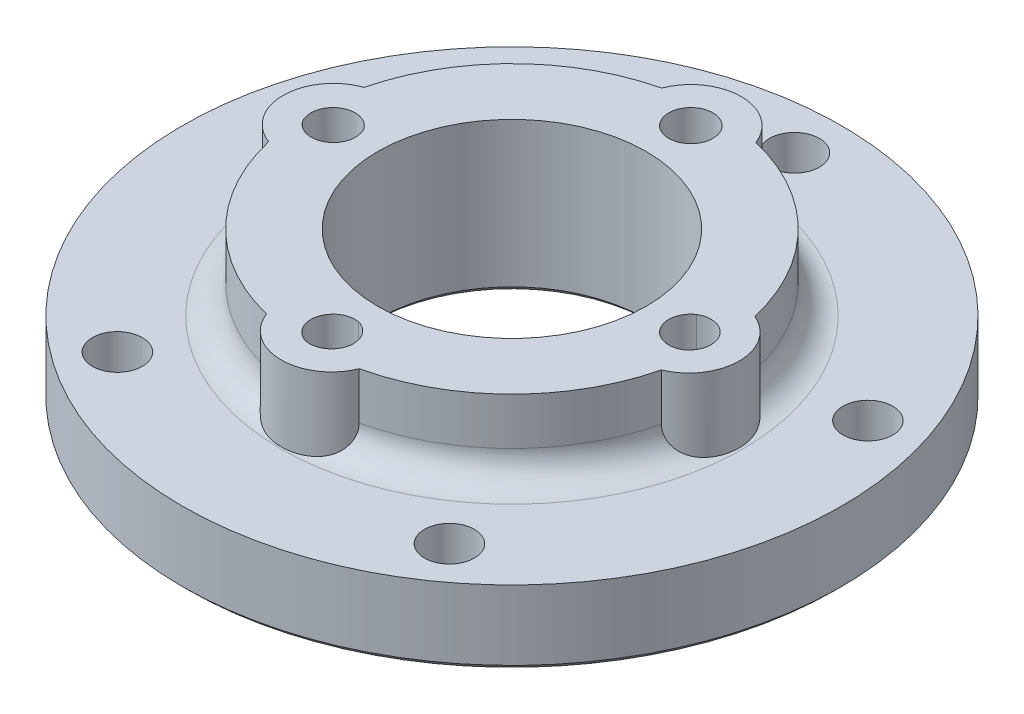
SolidWorks part; units mm, degrees
material "PETG"
ref_plane "Front Plane" through (0, 0, 0) normal (0, 0, 1) x (1, 0, 0)
ref_plane "Top Plane" through (0, 0, 0) normal (0, 1, 0) x (1, 0, 0)
ref_plane "Right Plane" through (0, 0, 0) normal (1, 0, 0) x (0, 0, -1)
sketch "Sketch2" plane through (0, 0, 0) normal (0, 1, 0) x (1, 0, 0)
  circle A0 centre (0, 0) radius 35
  circle A1 centre (0, 0) radius 30 construction
  circle A2 centre (0, 0) radius 21
  circle A3 centre (0, 30) radius 2.65
  circle A4 centre (28.5317, 9.2705) radius 2.65
  circle A5 centre (17.6336, -24.2705) radius 2.65
  circle A6 centre (-17.6336, -24.2705) radius 2.65
  circle A7 centre (-28.5317, 9.2705) radius 2.65
  point P22 (0, 0)
  dimension "D1" = 70
  dimension "D2" = 60
  dimension "D3" = 42
  dimension "D4" = 5.3
  dimension "D5" = 5
extrude "Boss-Extrude6" add sketch "Sketch2" along normal blind 8 separate body
sketch "Sketch3" plane through (0, 0, 0) normal (0, 1, 0) x (1, 0, 0)
  circle A0 centre (0, 0) radius 21 construction
  circle A1 centre (0, 0) radius 21 construction
  circle A2 centre (0, 0) radius 21.5
  circle A5 centre (0, 0) radius 14.25
  dimension "D1" = 28.5
  dimension "D2" = 0.5
extrude "Boss-Extrude7" add sketch "Sketch3" along normal blind 16
fillet "Fillet1" radius 3 1 edges at (0, 8, 21.5)
sketch "Sketch4" plane through (0, 16, 0) normal (0, 1, 0) x (1, 0, 0)
  circle A2 centre (0, 19) radius 2.35
  circle A5 centre (19, 0) radius 2.35
  circle A6 centre (0, -19) radius 2.35
  circle A7 centre (-19, 0) radius 2.35
  circle A8 centre (0, 0) radius 19 construction
  point P14 (0, 0)
  dimension "D1" = 38
  dimension "D2" = 4.7
  dimension "D3" = 4
extrude "Cut-Extrude1" cut sketch "Sketch4" against normal blind 15
sketch "Sketch7" plane through (0, 16, 0) normal (0, 1, 0) x (1, 0, 0)
  line L0 (-4.4779, 16.0723) -> (4.398, 15.9537)
  line L1 (15.9468, 4.3958) -> (15.8282, -4.4801)
  line L2 (4.2702, -16.0289) -> (-4.6057, -15.9103)
  line L3 (-16.1544, -4.3523) -> (-16.0358, 4.5236)
  circle A0 centre (18.8745, -0.0821) radius 2.35
  arc A1 (15.8282, -4.4801) -> (15.9468, 4.3958) centre (18.8745, -0.0821) ccw
  circle A2 centre (0, 19) radius 2.35 construction
  circle A3 centre (0, 19) radius 5.35
  arc A4 (4.398, 15.9537) -> (-4.4779, 16.0723) centre (0, 19) ccw
  circle A5 centre (0, 19) radius 2.35
  circle A6 centre (-0.2076, -18.9565) radius 2.35
  arc A7 (-4.6057, -15.9103) -> (4.2702, -16.0289) centre (-0.2076, -18.9565) ccw
  circle A8 centre (-19.0821, 0.1255) radius 2.35
  arc A9 (-16.0358, 4.5236) -> (-16.1544, -4.3523) centre (-19.0821, 0.1255) ccw
  point P25 (-0.1038, 0.0217)
  dimension "D1" = 3
  dimension "D2" = 4
extrude "Boss-Extrude9" add sketch "Sketch7" against normal up to surface (8 mm away) up to face at (0, 8, 24.5)
chamfer "Chamfer1" distance 0.6 angle 45 7 edges at (0, 0, 14.25) (-28.5317, 0, -6.6205) (-17.6336, 0, 26.9205) (17.6336, 0, 26.9205) (28.5317, 0, -6.6205) (0, 0, -27.35) (0, 0, 35)
